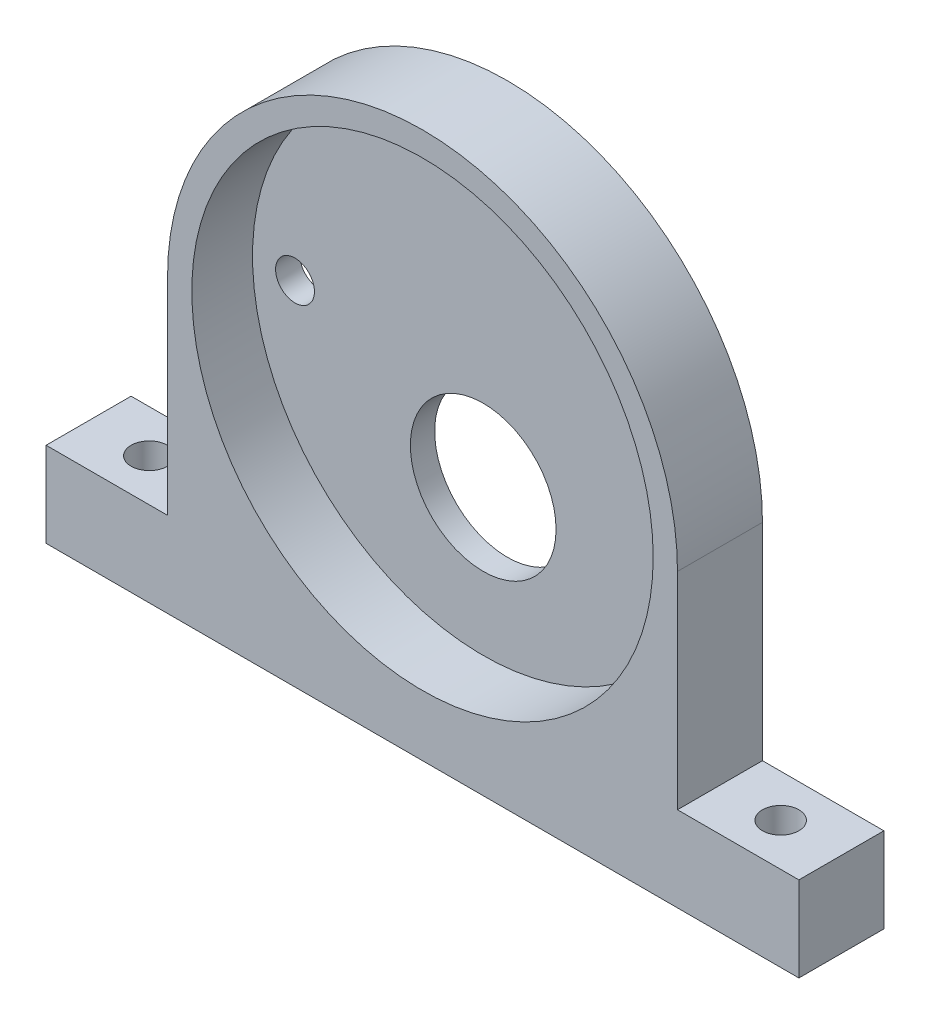
SolidWorks part; units mm, degrees
material "1060 Alloy"
ref_plane "Front Plane" through (0, 0, 0) normal (0, 0, 1) x (1, 0, 0)
ref_plane "Top Plane" through (0, 0, 0) normal (0, 1, 0) x (1, 0, 0)
ref_plane "Right Plane" through (0, 0, 0) normal (1, 0, 0) x (0, 0, -1)
sketch "Sketch1" plane through (0, 0, 0) normal (0, 0, 1) x (1, 0, 0)
  line L0 (-21, 20.5) -> (-21, 3.5)
  line L1 (-31, -3.5) -> (31, -3.5)
  line L2 (-31, -3.5) -> (-31, 3.5)
  line L3 (-31, 3.5) -> (31, 3.5)
  line L4 (31, -3.5) -> (31, 3.5)
  line L5 (-31, -3.5) -> (31, 3.5) construction
  line L6 (-31, 3.5) -> (31, -3.5) construction
  line L7 (21, 20.5) -> (21, 3.5)
  circle A0 centre (0, 20.5) radius 21
  point P0 (0, 0)
  dimension "D3" = 42
  dimension "D4" = 24
  dimension "D1" = 7
  dimension "D2" = 62
extrude "Boss-Extrude1" add sketch "Sketch1" along normal blind 7 contours A0 L3 | A0 L0 L3 | A0 L3 L7 | A0 L3 L2 L1 L4 | L3 A0 | A0 L1 L4 L3
sketch "Sketch2" plane through (0, 0, 7) normal (0, 0, 1) x (1, 0, 0)
  circle A0 centre (0, 20.5) radius 19
  dimension "D1" = 38
extrude "Cut-Extrude1" cut sketch "Sketch2" against normal blind 5
sketch "Sketch3" plane through (0, 0, 2) normal (0, 0, 1) x (1, 0, 0)
  line L0 (-31, -3.5) -> (31, -3.5) construction
  line L1 (0, 41.5) -> (0, -3.5) construction
  circle A0 centre (0, 13.5) radius 6
  circle A2 centre (15.5, 20.5) radius 1.6
  arc A3 (21, 20.5) -> (-21, 20.5) centre (0, 20.5) ccw construction
  circle A4 centre (-15.5, 20.5) radius 1.6
  dimension "D1" = 12
  dimension "D2" = 17
  dimension "D3" = 3.2
  dimension "D4" = 7
  dimension "D5" = 31
extrude "Cut-Extrude2" cut sketch "Sketch3" against normal blind 5
sketch "Sketch4" plane through (0, -3.5, 0) normal (0, -1, 0) x (1, 0, 0)
  line L0 (0, 0) -> (0, 7) construction
  line L1 (-31, 7) -> (31, 7) construction
  line L2 (31, 7) -> (31, 0) construction
  circle A0 centre (14, 3.5) radius 1.5
  circle A1 centre (-14, 3.5) radius 1.5
  point P10 (31, 3.5)
  dimension "D1" = 14
  dimension "D2" = 3
hole_wizard "M3 Tapped Hole1" positions "3DSketch1" profile "Sketch5" tap size "M3" standard "ISO"
sketch3d "3DSketch1"
  point P0 (-14, -3.5, 3.5)
  point P3 (14, -3.5, 3.5)
sketch "Sketch5" plane through (-14, -3.5, 3.5) normal (1, 0, 0) x (0, 0, -1)
  line L0 (0, 0) -> (0, 5.7511)
  line L1 (0, 5.7511) -> (1.25, 5)
  line L2 (1.25, 5) -> (1.25, 0)
  line L5 (1.25, 0) -> (0, 0)
  line L10 (0, 5.7511) -> (-1.25, 5) construction
  line L11 (0, -6.35) -> (0, 107.95) construction
  dimension "Tap Drill Dia." = 2.5
  dimension "Tap Drill Depth" = 5
  dimension "Drill Angle" = 118
cosmetic thread "Hole Thread2" parameters "D1"=6, "D2"=3
cosmetic thread "Hole Thread3" parameters "D1"=6, "D2"=3
sketch "Sketch6" plane through (0, 3.5, 0) normal (0, 1, 0) x (1, 0, 0)
  line L0 (0, 0) -> (0, -7) construction
  circle A0 centre (-26, -3.5) radius 1.5
  circle A1 centre (26, -3.5) radius 1.5
  point P8 (0, -3.5)
  dimension "D1" = 3
  dimension "D2" = 26
extrude "Cut-Extrude3" cut sketch "Sketch6" against normal up to surface (7 mm away) up to face at (-14, -3.5, 2.25)
